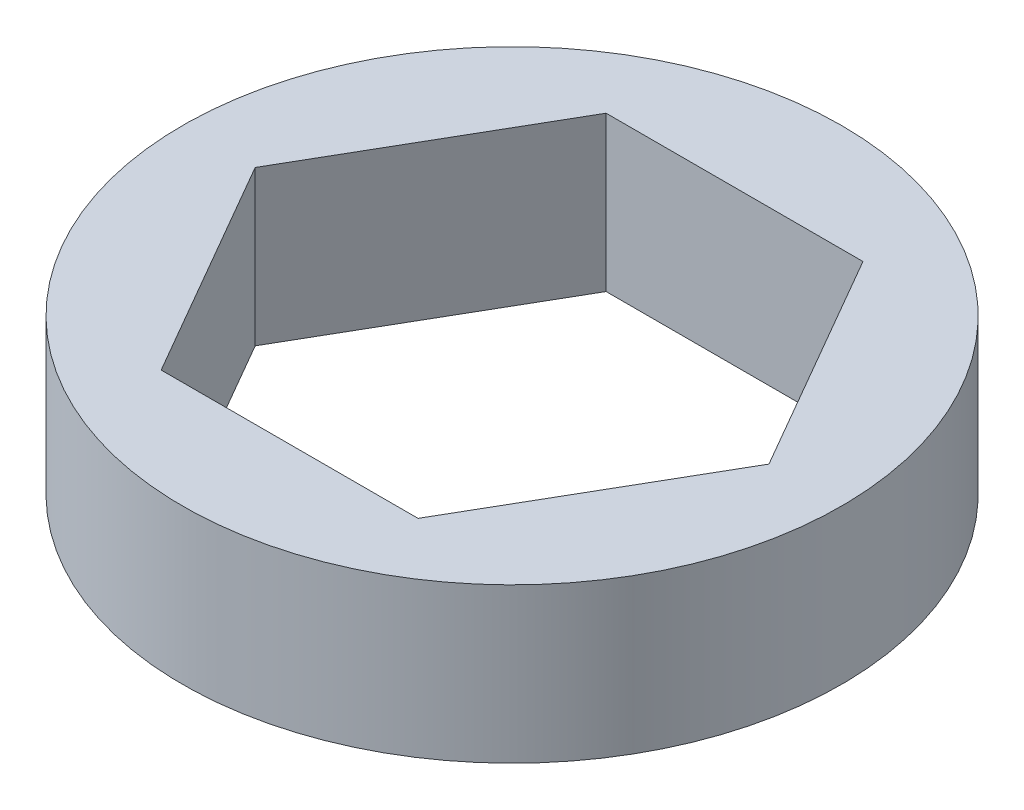
SolidWorks part; units mm, degrees
ref_plane "Front Plane" through (0, 0, 0) normal (0, 0, 1) x (1, 0, 0)
ref_plane "Top Plane" through (0, 0, 0) normal (0, 1, 0) x (1, 0, 0)
ref_plane "Right Plane" through (0, 0, 0) normal (1, 0, 0) x (0, 0, -1)
sketch "Sketch1" plane through (0, 0, 0) normal (0, 1, 0) x (1, 0, 0)
  line L1 (7.9189, 0) -> (3.9595, 6.858)
  line L2 (3.9595, 6.858) -> (-3.9595, 6.858)
  line L3 (-3.9595, 6.858) -> (-7.9189, 0)
  line L4 (-7.9189, 0) -> (-3.9595, -6.858)
  line L5 (-3.9595, -6.858) -> (3.9595, -6.858)
  line L6 (3.9595, -6.858) -> (7.9189, 0)
  circle A0 centre (0, 0) radius 6.858 construction
  circle A1 centre (0, 0) radius 10.16
  dimension "D2" = 20.32
  dimension "D1" = 13.716
extrude "Boss-Extrude1" add sketch "Sketch1" along normal blind 4.7625
